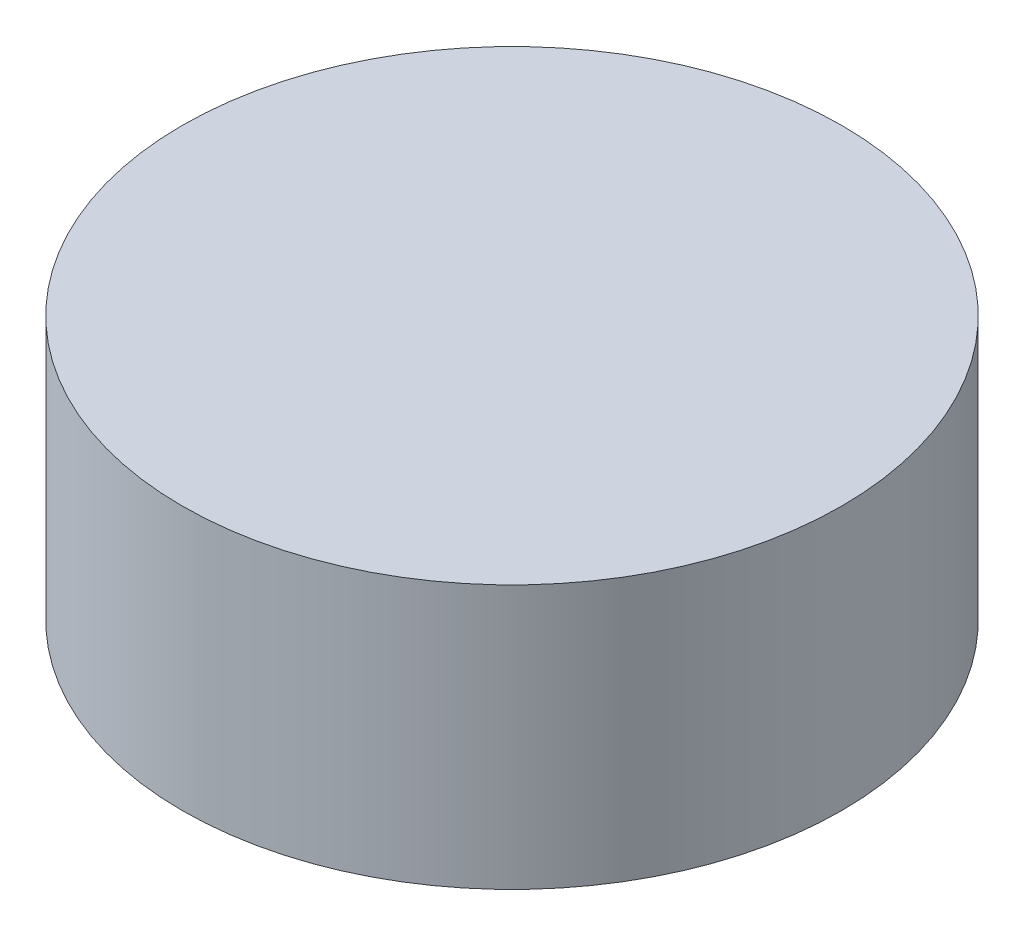
SolidWorks part; units mm, degrees
ref_plane "Płaszczyzna przednia" through (0, 0, 0) normal (0, 0, 1) x (1, 0, 0)
ref_plane "Płaszczyzna górna" through (0, 0, 0) normal (0, 1, 0) x (1, 0, 0)
ref_plane "Płaszczyzna prawa" through (0, 0, 0) normal (1, 0, 0) x (0, 0, -1)
sketch "Sketch1" plane through (0, 0, 0) normal (0, 1, 0) x (1, 0, 0)
  circle A0 centre (0, 0) radius 2.5
  dimension "D1" = 5
extrude "Boss-Extrude1" add sketch "Sketch1" along normal blind 2
